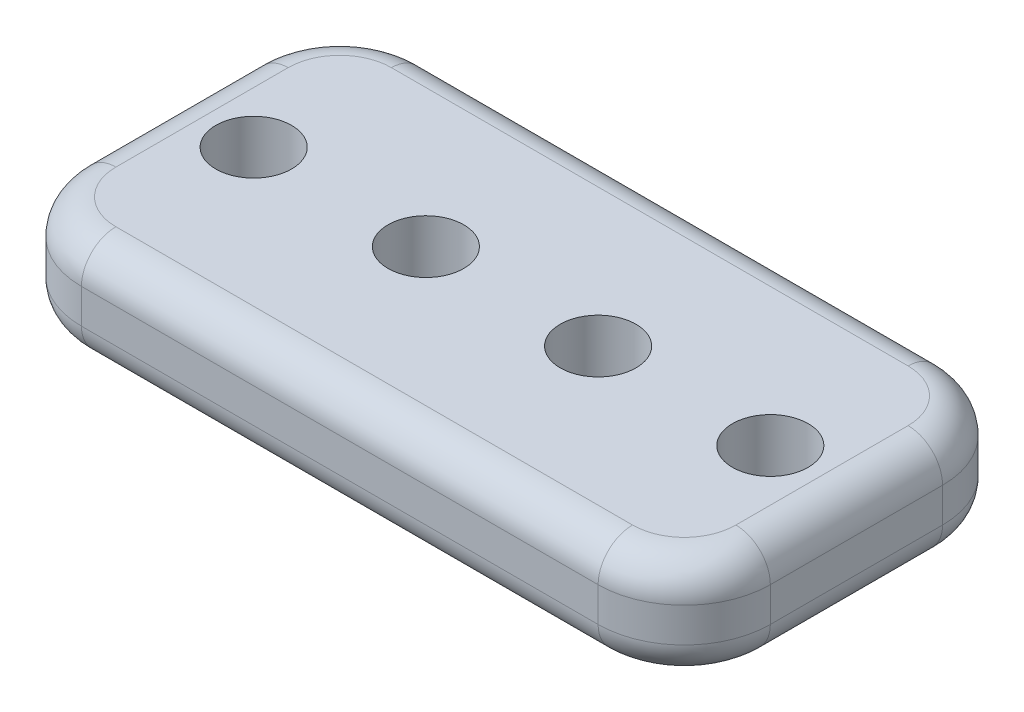
SolidWorks part; units mm, degrees
ref_plane "前视基准面" through (0, 0, 0) normal (0, 0, 1) x (1, 0, 0)
ref_plane "上视基准面" through (0, 0, 0) normal (0, 1, 0) x (1, 0, 0)
ref_plane "右视基准面" through (0, 0, 0) normal (1, 0, 0) x (0, 0, -1)
other "Configuration Table"
sketch "草图1" plane through (0, 0, 0) normal (0, 1, 0) x (1, 0, 0)
  line L0 (0, -55) -> (0, 55) construction
  line L1 (-7.5, 5) -> (7.5, 5)
  line L2 (-10, 2.5) -> (-10, -2.5)
  line L3 (-7.5, -5) -> (7.5, -5)
  line L4 (10, 2.5) -> (10, -2.5)
  line L5 (-55, 0) -> (55, 0) construction
  arc A0 (-7.5, 5) -> (-10, 2.5) centre (-7.5, 2.5) ccw
  arc A1 (-10, -2.5) -> (-7.5, -5) centre (-7.5, -2.5) ccw
  arc A2 (7.5, -5) -> (10, -2.5) centre (7.5, -2.5) ccw
  arc A4 (10, 2.5) -> (7.5, 5) centre (7.5, 2.5) ccw
  point P18 (0.7178, 6.8837)
  dimension "D5" = 2.5
  dimension "D1" = 2.5
  dimension "D13" = 2.5
  dimension "D14" = 2.5
  dimension "D15" = 2.5
  dimension "D16" = 2.5
  dimension "D2" = 2.5
  dimension "D3" = 10
  dimension "D4" = 5
  dimension "D6" = 2.5
  dimension "D7" = 2.5
  dimension "D8" = 2.5
  dimension "D9" = 2.5
  dimension "D10" = 2.5
  dimension "D11" = 5
  dimension "D12" = 20
extrude "凸台-拉伸1" add sketch "草图1" along normal blind 3
sketch "草图2" plane through (0, 3, 0) normal (0, 1, 0) x (1, 0, 0)
  line L0 (-1.65, 0) -> (1.65, 0) construction
  line L1 (0, -1.65) -> (0, 1.65) construction
  point P0 (-7.5, 0)
  point P4 (-2.5, 0)
  dimension "D1" = 2.5
  dimension "D2" = 5
hole_wizard "Ø2.2 (2.2) Diameter Hole1" positions "草图2" profile "草图3" hole size "Ø2.2" standard "ANSI Metric" end condition up to next
sketch "草图3" plane through (-7.5, 3, 0) normal (1, 0, 0) x (0, 0, 1)
  line L0 (0, 0) -> (0, 3)
  line L1 (0, 3) -> (1.1, 3)
  line L2 (1.1, 3) -> (1.1, 0)
  line L5 (1.1, 0) -> (0, 0)
  line L11 (0, -6.35) -> (0, 107.95) construction
  dimension "Thru Hole Dia." = 2.2
  dimension "Thru Hole Depth" = 3
mirror "镜向1" about plane through (0, 0, 0) normal (1, 0, 0) of "Ø2.2 (2.2) Diameter Hole1"
fillet "圆角1" radius 1 16 edges at (9.2678, 0, -4.2678) (10, 0, 0) (9.2678, 0, 4.2678) (0, 0, 5) (-9.2678, 0, 4.2678) (-10, 0, 0) (-9.2678, 0, -4.2678) (0, 0, -5) (9.2678, 3, -4.2678) (10, 3, 0) (9.2678, 3, 4.2678) (0, 3, 5) (-9.2678, 3, 4.2678) (-10, 3, 0) (0, 3, -5) (-9.2678, 3, -4.2678)
